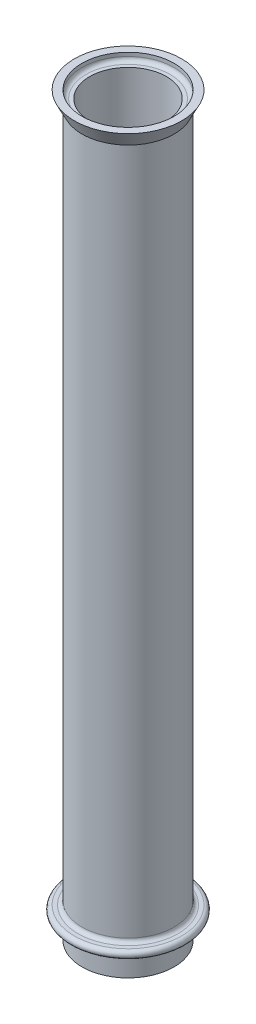
SolidWorks part; units mm, degrees
ref_plane "Front Plane" through (0, 0, 0) normal (0, 0, 1) x (1, 0, 0)
ref_plane "Top Plane" through (0, 0, 0) normal (0, 1, 0) x (1, 0, 0)
ref_plane "Right Plane" through (0, 0, 0) normal (1, 0, 0) x (0, 0, -1)
sketch "Sketch1" plane through (0, 0, 0) normal (0, 0, 1) x (1, 0, 0)
  line L0 (-7.9375, 0) -> (-7.9375, 150.8125)
  line L5 (-7.9375, 0) -> (-9.525, 0)
  line L6 (0, 0) -> (0, 152.4) construction
  line L8 (-9.525, 0) -> (-9.525, 3.9687)
  line L9 (-7.9375, 0) -> (0, 0) construction
  line L10 (-9.525, 152.4) -> (0, 152.4) construction
  line L11 (-10.3188, 4.7625) -> (-11.1125, 4.7625)
  line L13 (-11.1125, 6.35) -> (-10.3187, 6.35)
  line L14 (-9.525, 7.1437) -> (-9.525, 149.225)
  line L18 (-7.9375, 150.8125) -> (0, 150.8125) construction
  line L20 (-11.1125, 152.4) -> (-9.525, 152.4)
  line L21 (-9.525, 149.225) -> (-11.1125, 152.4)
  line L22 (-7.9375, 150.8125) -> (-8.6995, 150.8125)
  line L24 (-9.525, 152.4) -> (-9.525, 151.638)
  arc A0 (-10.3187, 6.35) -> (-9.525, 7.1437) centre (-10.3187, 7.1437) ccw
  arc A1 (-11.1125, 4.7625) -> (-11.1125, 6.35) centre (-11.1125, 5.5562) cw
  arc A5 (-10.3188, 4.7625) -> (-9.525, 3.9687) centre (-10.3187, 3.9687) cw
  arc A7 (-8.6995, 150.8125) -> (-9.525, 151.638) centre (-8.6995, 151.638) cw
  point P17 (-9.525, 6.35)
  dimension "D8" = 0.7937
  dimension "D9" = 0.7937
  dimension "D7" = 0.8255
  dimension "D10" = 11.1125
  dimension "D12" = 0.7937
  dimension "D14" = 1.5875
  dimension "D1" = 9.525
  dimension "D2" = 1.5875
  dimension "D3" = 152.4
  dimension "D4" = 0.7938
  dimension "D5" = 1.5875
  dimension "D6" = 4.7625
  dimension "D11" = 3.175
  dimension "D13" = 1.5875
revolve "Revolve1" add sketch "Sketch1" angle 360 about L6
